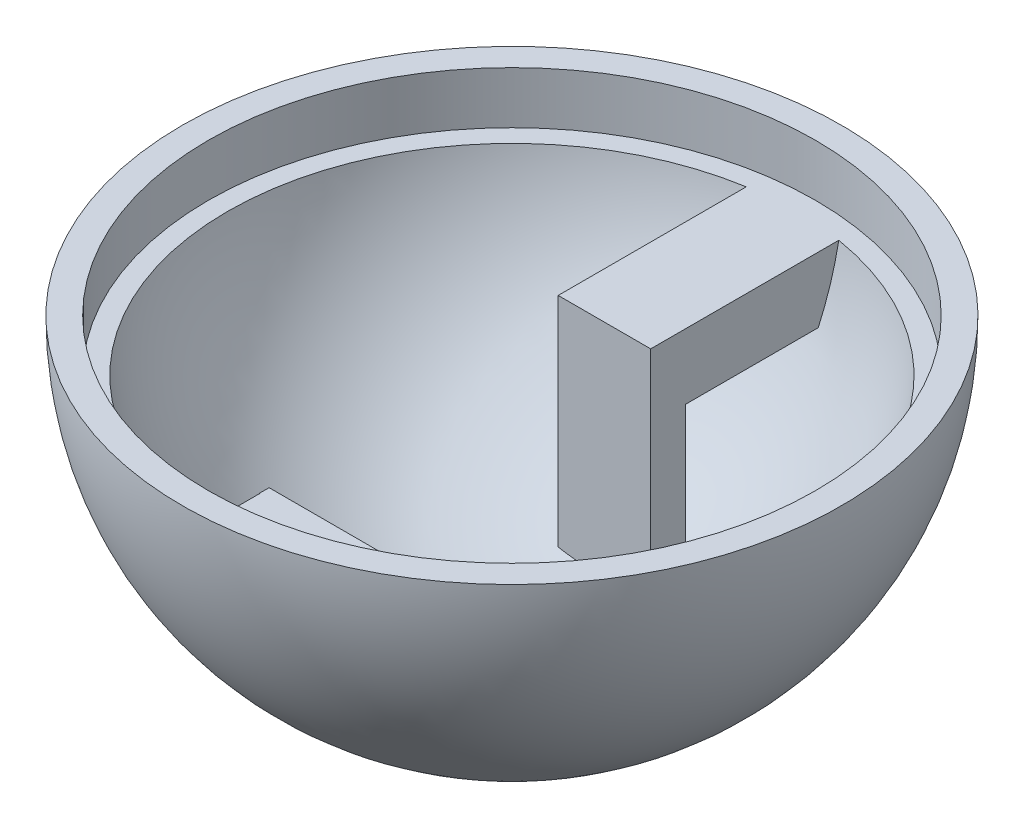
SolidWorks part; units mm, degrees
ref_plane "Front Plane" through (0, 0, 0) normal (0, 0, 1) x (1, 0, 0)
ref_plane "Top Plane" through (0, 0, 0) normal (0, 1, 0) x (1, 0, 0)
ref_plane "Right Plane" through (0, 0, 0) normal (1, 0, 0) x (0, 0, -1)
sketch "Sketch1" plane through (0, 0, 0) normal (0, 0, 1) x (1, 0, 0)
  line L0 (0, 0) -> (-25, 0) construction
  line L1 (0, 0) -> (0, -50) construction
  line L2 (0, -25) -> (0, -28.5)
  line L3 (0, -28.5) -> (-0.0005, -28.5222)
  line L4 (-26.25, 0) -> (-26.25, -4.5)
  line L5 (-26.25, 0) -> (-50, 0) construction
  line L6 (-26.25, -4.5) -> (-24.5917, -4.5)
  line L7 (-26.25, 0) -> (-28.5, 0)
  arc A0 (-24.5917, -4.5) -> (0, -25) centre (0, 0) ccw
  arc A1 (-28.5, 0) -> (0, -28.5) centre (0, 0) ccw
  dimension "D1" = 3.5
  dimension "D2" = 25
  dimension "D3" = 3.5
  dimension "D4" = 4.5
  dimension "D5" = 2.25
  dimension "D6" = 28.5
  dimension "D7" = 1.25
revolve "Revolve1" add sketch "Sketch1" angle 360 about L1
sketch "Sketch2" plane through (0, 0, 0) normal (0, 1, 0) x (1, 0, 0)
  line L0 (-28.5, 0) -> (28.5, 0) construction
  line L1 (0, 28.5) -> (0, -28.5) construction
  line L2 (-5, -9.5) -> (-5, -5.5)
  line L3 (-11, -9.5) -> (-5, -9.5)
  line L4 (-11, -9.5) -> (-11, -11)
  line L5 (-11, -11) -> (11, -11)
  line L6 (11, -9.5) -> (11, -11)
  line L7 (-5, -5.5) -> (5, -5.5)
  line L8 (5, -5.5) -> (5, -9.5)
  line L9 (5, -9.5) -> (11, -9.5)
  circle A0 centre (0, 0) radius 28.5 construction
  point P16 (-11, -10.25)
  dimension "D1" = 11
  dimension "D2" = 1.5
  dimension "D3" = 5
  dimension "D4" = 5
  dimension "D5" = 11
  dimension "D6" = 11
  dimension "D7" = 5.5
  dimension "D8" = 22
extrude "Cut-Extrude1" cut sketch "Sketch2" against normal blind 33
sketch "Sketch3" plane through (0, -4.5, 0) normal (0, 1, 0) x (1, 0, 0)
  line L0 (11, -11) -> (-11, -11) construction
  line L1 (0, -11) -> (0, -20.0184) construction
  line L2 (9, -12) -> (-9, -12) construction
  line L4 (9, -12) -> (-9, -12)
  line L5 (9, -12) -> (9, -12.819)
  line L6 (9, -12.819) -> (-9, -12.819)
  line L7 (-9, -12) -> (-9, -12.819)
  dimension "D1" = 1
  dimension "D2" = 18
  dimension "D3" = 0.819
extrude "Boss-Extrude2" add sketch "Sketch3" against normal blind 10.5551 from offset 6.8984 offset against normal yes
sketch "Sketch4" plane through (0, -4.5, 0) normal (0, 1, 0) x (1, 0, 0)
  line L0 (0, 28.9036) -> (0, -29.1182) construction
  line L1 (-28.5, 0) -> (29.0581, 0) construction
  line L3 (-4, 8) -> (4, 8)
  line L4 (-4, 8) -> (-4, 11)
  line L5 (-4, 11) -> (4, 11)
  line L6 (4, 8) -> (4, 11)
  line L7 (-4, 8) -> (4, 11) construction
  line L8 (-4, 11) -> (4, 8) construction
  circle A0 centre (0, 0) radius 28.5 construction
  point P7 (0, 9.5)
  point P12 (0, 8)
  dimension "D1" = 8
  dimension "D2" = 3
  dimension "D3" = 8
extrude "Boss-Extrude3" add sketch "Sketch4" against normal blind 21
sketch "Sketch6" plane through (0, 0, -11) normal (0, 0, -1) x (-1, 0, 0)
  line L0 (-4, -22.0907) -> (-4, -4.5) construction
  line L1 (4, -4.5) -> (-4, -4.5)
  line L2 (4, -4.5) -> (4, -10.1612)
  line L3 (4, -10.1612) -> (-4, -10.1612)
  line L4 (-4, -4.5) -> (-4, -10.1612)
extrude "Boss-Extrude4" add sketch "Sketch6" along normal blind 15
sketch "Sketch7" plane through (0, 0, 12.819) normal (0, 0, 1) x (1, 0, 0)
  line L1 (9, -11.3984) -> (-8.9673, -11.3984)
  line L2 (9, -11.3984) -> (9, -11.8984)
  line L3 (9, -11.8984) -> (-8.9673, -11.8984)
  line L4 (-8.9673, -11.3984) -> (-8.9673, -11.8984)
  point P5 (9, -13.0342)
  point P6 (0, 0)
  point P7 (9, -11.621)
  dimension "D1" = 0.5
extrude "Boss-Extrude7" add sketch "Sketch7" along normal blind 11
